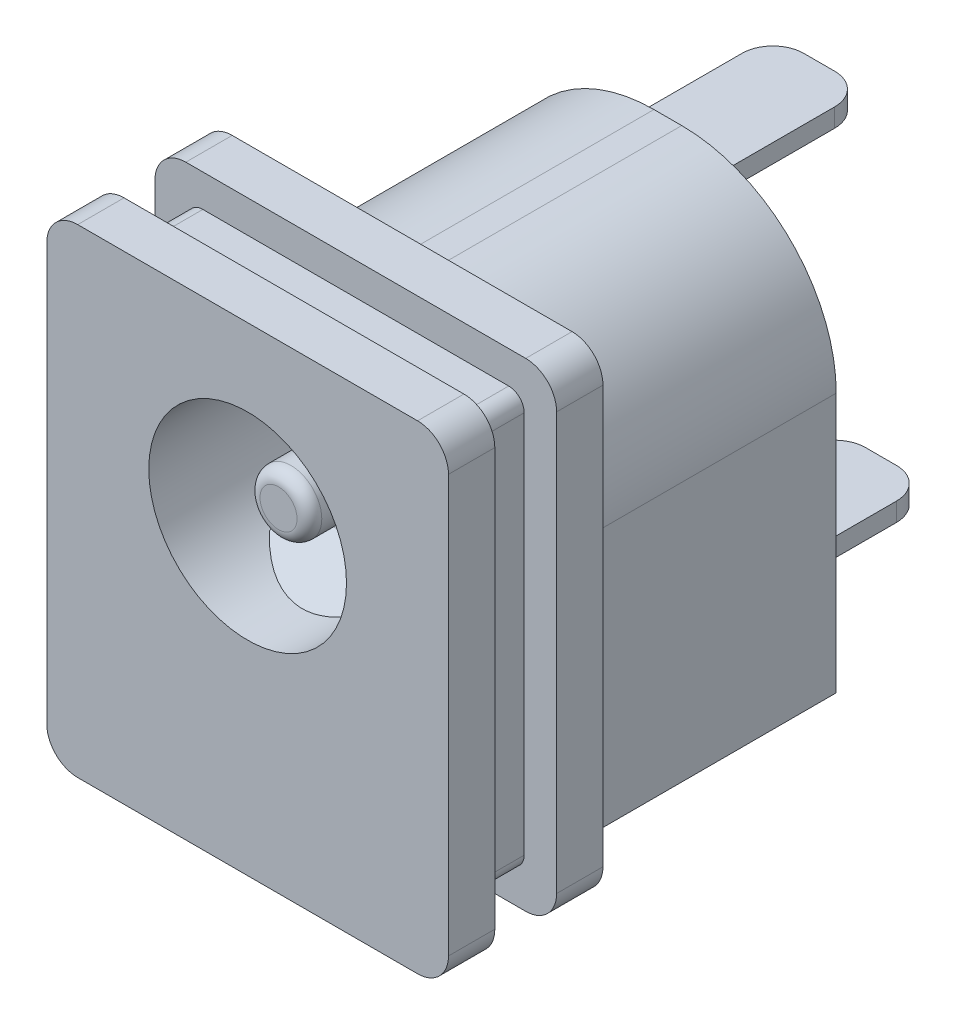
SolidWorks part; units mm, degrees
ref_plane "Спереди" through (0, 0, 0) normal (0, 0, 1) x (1, 0, 0)
ref_plane "Сверху" through (0, 0, 0) normal (0, 1, 0) x (1, 0, 0)
ref_plane "Справа" through (0, 0, 0) normal (1, 0, 0) x (0, 0, -1)
sketch "Эскиз1" plane through (0, 0, 0) normal (0, 0, 1) x (1, 0, 0)
  line L1 (5.5, -7.75) -> (-5.5, -7.75)
  line L2 (6.5, -6.75) -> (6.5, 6.75)
  line L3 (5.5, 7.75) -> (-5.5, 7.75)
  line L4 (-6.5, -6.75) -> (-6.5, 6.75)
  line L5 (6.5, -7.75) -> (-6.5, 7.75) construction
  line L6 (6.5, 7.75) -> (-6.5, -7.75) construction
  arc A0 (-5.5, -7.75) -> (-6.5, -6.75) centre (-5.5, -6.75) cw
  arc A1 (5.5, -7.75) -> (6.5, -6.75) centre (5.5, -6.75) ccw
  arc A2 (6.5, 6.75) -> (5.5, 7.75) centre (5.5, 6.75) ccw
  arc A3 (-5.5, 7.75) -> (-6.5, 6.75) centre (-5.5, 6.75) ccw
  point P0 (0, 0)
  dimension "D3" = 1
  dimension "D1" = 13
  dimension "D2" = 15.5
extrude "Бобышка-Вытянуть1" add sketch "Эскиз1" along normal blind 1.5
sketch "Эскиз2" plane through (0, 0, 0) normal (0, 0, 1) x (1, 0, 0)
  line L1 (4.95, -6.7) -> (-4.95, -6.7)
  line L2 (5.45, -6.2) -> (5.45, 6.2)
  line L3 (4.95, 6.7) -> (-4.95, 6.7)
  line L4 (-5.45, -6.2) -> (-5.45, 6.2)
  line L5 (5.45, -6.7) -> (-5.45, 6.7) construction
  line L6 (5.45, 6.7) -> (-5.45, -6.7) construction
  arc A0 (-4.95, -6.7) -> (-5.45, -6.2) centre (-4.95, -6.2) cw
  arc A1 (4.95, -6.7) -> (5.45, -6.2) centre (4.95, -6.2) ccw
  arc A2 (5.45, 6.2) -> (4.95, 6.7) centre (4.95, 6.2) ccw
  arc A3 (-4.95, 6.7) -> (-5.45, 6.2) centre (-4.95, 6.2) ccw
  point P0 (0, 0)
  dimension "D3" = 0.5
  dimension "D1" = 10.9
  dimension "D2" = 13.4
extrude "Бобышка-Вытянуть2" add sketch "Эскиз2" against normal blind 2
sketch "Эскиз3" plane through (0, 0, -2) normal (0, 0, -1) x (-1, 0, 0)
  line L1 (-5.5, -7.75) -> (5.5, -7.75)
  line L2 (-6.5, -6.75) -> (-6.5, 6.75)
  line L3 (-5.5, 7.75) -> (5.5, 7.75)
  line L4 (6.5, -6.75) -> (6.5, 6.75)
  line L5 (-6.5, -7.75) -> (6.5, 7.75) construction
  line L6 (-6.5, 7.75) -> (6.5, -7.75) construction
  arc A0 (5.5, -7.75) -> (6.5, -6.75) centre (5.5, -6.75) ccw
  arc A1 (-5.5, -7.75) -> (-6.5, -6.75) centre (-5.5, -6.75) cw
  arc A2 (-6.5, 6.75) -> (-5.5, 7.75) centre (-5.5, 6.75) cw
  arc A3 (5.5, 7.75) -> (6.5, 6.75) centre (5.5, 6.75) cw
  point P0 (0, 0)
  dimension "D3" = 1
  dimension "D1" = 13
  dimension "D2" = 15.5
extrude "Бобышка-Вытянуть3" add sketch "Эскиз3" along normal blind 1.5
sketch "Эскиз4" plane through (0, 0, -3.5) normal (0, 0, -1) x (-1, 0, 0)
  line L1 (-5.45, -6.7) -> (5.45, -6.7)
  line L2 (-5.45, -6.7) -> (-5.45, 1.7)
  line L3 (-0.45, 6.7) -> (0.45, 6.7)
  line L4 (5.45, -6.7) -> (5.45, 1.7)
  line L5 (-5.45, -6.7) -> (5.45, 6.7) construction
  line L6 (-5.45, 6.7) -> (5.45, -6.7) construction
  arc A0 (-5.45, 1.7) -> (-0.45, 6.7) centre (-0.45, 1.7) cw
  arc A1 (0.45, 6.7) -> (5.45, 1.7) centre (0.45, 1.7) cw
  point P0 (0, 0)
  dimension "D3" = 5
  dimension "D1" = 10.9
  dimension "D2" = 13.4
extrude "Бобышка-Вытянуть4" add sketch "Эскиз4" along normal blind 8.6
sketch "Эскиз5" plane through (0, 0, 1.5) normal (0, 0, 1) x (1, 0, 0)
  line L0 (-5.5, -7.75) -> (5.5, -7.75) construction
  circle A0 centre (0, 2.05) radius 3.2
  dimension "D1" = 0
  dimension "D3" = 6.4
  dimension "D2" = 9.8
extrude "Вырез-Вытянуть1" cut sketch "Эскиз5" against normal blind 10
sketch "Эскиз6" plane through (0, 0, -8.5) normal (0, 0, 1) x (1, 0, 0)
  line L0 (-5.5, -7.75) -> (5.5, -7.75) construction
  circle A0 centre (0, 2.05) radius 1
  dimension "D1" = 0
  dimension "D3" = 2
  dimension "D2" = 9.8
extrude "Бобышка-Вытянуть5" add sketch "Эскиз6" along normal blind 9
fillet "Скругление1" radius 0.4 1 edges at (1, 2.05, 0.5)
sketch "Эскиз8" plane through (0, 0, 0) normal (0, 0, 1) x (1, 0, 0)
  line L1 (-2, -1.35) -> (2, -1.35)
  line L2 (-2, -1.35) -> (-2, -1.65)
  line L3 (-2, -1.65) -> (2, -1.65)
  line L4 (2, -1.35) -> (2, -1.65)
  line L5 (-2, -1.35) -> (2, -1.65) construction
  line L6 (-2, -1.65) -> (2, -1.35) construction
  point P0 (0, -1.5)
  dimension "D1" = 0
  dimension "D2" = 0.3
  dimension "D3" = 4
  dimension "D4" = 1.5
sketch "Эскиз9" plane through (0, 0, 0) normal (1, 0, 0) x (0, 0, -1)
  line L0 (0, -1.5) -> (1.8667, -0.1)
  line L1 (2.1667, 0) -> (2.8333, 0)
  line L2 (3.1333, -0.1) -> (4.8667, -1.4)
  line L3 (5.1667, -1.5) -> (8.1667, -1.5)
  arc A0 (4.8667, -1.4) -> (5.1667, -1.5) centre (5.1667, -1) ccw
  arc A1 (2.8333, 0) -> (3.1333, -0.1) centre (2.8333, -0.5) cw
  arc A2 (1.8667, -0.1) -> (2.1667, 0) centre (2.1667, -0.5) cw
  point P9 (5, -1.5)
  point P12 (3, 0)
  point P15 (2, 0)
  dimension "D7" = 0.5
  dimension "D1" = 2
  dimension "D2" = 1.5
  dimension "D3" = 2
  dimension "D4" = 1.5
  dimension "D5" = 1.5
  dimension "D6" = 1
  dimension "D8" = 3
sweep "По траектории1" add profiles "Эскиз8" path "Эскиз9"
sketch "Эскиз11" plane through (0, 0, -12.1) normal (0, 0, -1) x (-1, 0, 0)
  line L0 (-5.5, -7.75) -> (5.5, -7.75) construction
  line L1 (-3.5, -4.25) -> (-0.5, -4.25)
  line L2 (-3.5, -4.25) -> (-3.5, -4.85)
  line L3 (-3.5, -4.85) -> (-0.5, -4.85)
  line L4 (-0.5, -4.25) -> (-0.5, -4.85)
  line L5 (-3.5, -4.25) -> (-0.5, -4.85) construction
  line L6 (-3.5, -4.85) -> (-0.5, -4.25) construction
  line L7 (0.5, -1.05) -> (3.5, -1.05)
  line L8 (0.5, -1.05) -> (0.5, -1.65)
  line L9 (0.5, -1.65) -> (3.5, -1.65)
  line L10 (3.5, -1.05) -> (3.5, -1.65)
  line L11 (0.5, -1.05) -> (3.5, -1.65) construction
  line L12 (0.5, -1.65) -> (3.5, -1.05) construction
  line L13 (-1.5, 5.8) -> (1.5, 5.8)
  line L14 (-1.5, 5.8) -> (-1.5, 5.2)
  line L15 (-1.5, 5.2) -> (1.5, 5.2)
  line L16 (1.5, 5.8) -> (1.5, 5.2)
  line L17 (-1.5, 5.8) -> (1.5, 5.2) construction
  line L18 (-1.5, 5.2) -> (1.5, 5.8) construction
  point P0 (-2, -4.55)
  point P5 (2, -1.35)
  point P10 (0, 5.5)
  dimension "D1" = 0
  dimension "D2" = 3
  dimension "D3" = 0.6
  dimension "D4" = 5.5
  dimension "D5" = 3
  dimension "D6" = 3
  dimension "D7" = 0.6
  dimension "D8" = 0.6
  dimension "D9" = 2
  dimension "D10" = 2
  dimension "D11" = 3.2
  dimension "D12" = 6.4
extrude "Бобышка-Вытянуть6" add sketch "Эскиз11" along normal blind 4.9
sketch "Эскиз12" plane through (0, 0, -12.1) normal (0, 0, -1) x (-1, 0, 0)
  line L1 (-1.5, 5.8) -> (1.5, 5.8)
  line L2 (-1.5, 5.8) -> (-1.5, 0.3)
  line L3 (-1.5, 0.3) -> (1.5, 0.3)
  line L4 (1.5, 5.8) -> (1.5, 0.3)
  line L5 (-1.5, 5.8) -> (-1.5, 5.2) construction
  line L6 (1.5, 5.2) -> (1.5, 5.8) construction
  line L7 (1.5, 5.8) -> (-1.5, 5.8) construction
  line L8 (-5.45, -6.7) -> (5.45, -6.7) construction
  dimension "D1" = 0
  dimension "D2" = 0
  dimension "D3" = 0
  dimension "D4" = 7
extrude "Бобышка-Вытянуть7" add sketch "Эскиз12" along normal blind 0.8
sketch "Эскиз13" plane through (0, 0, -12.1) normal (0, 0, -1) x (-1, 0, 0)
  line L0 (-5.5, -7.75) -> (5.5, -7.75) construction
  circle A0 centre (0, 2.05) radius 1.25
  dimension "D1" = 0
  dimension "D3" = 2.5
  dimension "D2" = 9.8
extrude "Бобышка-Вытянуть8" add sketch "Эскиз13" along normal blind 1.6
fillet "Скругление2" radius 1 2 edges at (-1.5, 0.3, -12.5) (1.5, 0.3, -12.5)
fillet "Скругление3" radius 1 6 edges at (-1.5, 5.5, -17) (1.5, 5.5, -17) (-3.5, -1.35, -17) (-0.5, -1.35, -17) (0.5, -4.55, -17) (3.5, -4.55, -17)
